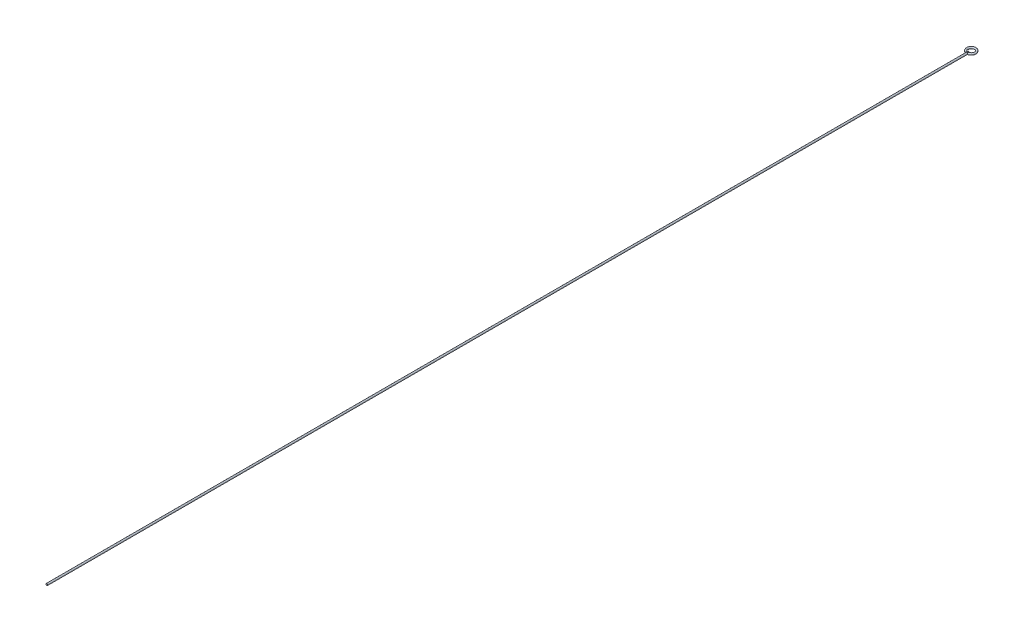
SolidWorks part; units mm, degrees
material "AISI 1010 Steel, hot rolled bar"
ref_plane "Front Plane" through (0, 0, 0) normal (0, 0, 1) x (1, 0, 0)
ref_plane "Top Plane" through (0, 0, 0) normal (0, 1, 0) x (1, 0, 0)
ref_plane "Right Plane" through (0, 0, 0) normal (1, 0, 0) x (0, 0, -1)
sketch "Sketch1" plane through (0, 0, 0) normal (0, 0, 1) x (1, 0, 0)
  circle A0 centre (0, 0) radius 2
  dimension "D1" = 4
extrude "Boss-Extrude1" add sketch "Sketch1" along normal blind 2125 from offset 6
sketch "Sketch4" plane through (0, 0, 0) normal (0, 0, -1) x (-1, 0, 0)
  line L0 (0, 3.776) -> (0, -3.776)
  circle A0 centre (-9, 0) radius 2
  point P4 (0, 0)
  dimension "D1" = 9
revolve "Revolve1" add sketch "Sketch4" angle 360 about L0
sketch "Sketch7" plane through (0, 0, 0) normal (0, 1, 0) x (1, 0, 0)
  circle A0 centre (0, -9) radius 2
  dimension "D1" = 4
  dimension "D2" = 9
extrude "Boss-Extrude2" add sketch "Sketch7" along normal blind 2.1
sketch "Sketch8" plane through (0, 0, 0) normal (0, 1, 0) x (1, 0, 0)
  line L0 (0, 0) -> (0, -1800) construction
  dimension "D1" = 1800
